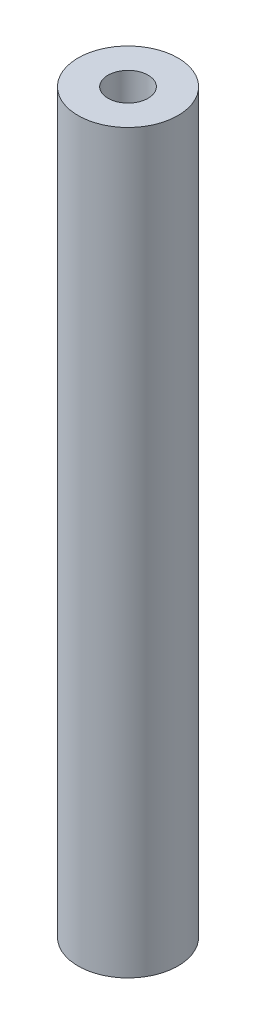
SolidWorks part; units mm, degrees
material "6061 Alloy"
ref_plane "Front" through (0, 0, 0) normal (0, 0, 1) x (1, 0, 0)
ref_plane "Top" through (0, 0, 0) normal (0, 1, 0) x (1, 0, 0)
ref_plane "Right" through (0, 0, 0) normal (1, 0, 0) x (0, 0, -1)
sketch "Sketch1" plane through (0, 0, 0) normal (0, 1, 0) x (1, 0, 0)
  circle A0 centre (0, 0) radius 6.35
  dimension "D1" = 12.7
extrude "Boss-Extrude1" add sketch "Sketch1" along normal blind 93.6625
hole_wizard "1/4-20 Tapped Hole1" positions "Sketch2" profile "Sketch3" tap size "1/4-20" standard "ANSI Inch"
sketch "Sketch2" plane through (0, 93.6625, 0) normal (0, 1, 0) x (1, 0, 0)
  point P0 (0, 0)
sketch "Sketch3" plane through (0, 93.6625, 0) normal (1, 0, 0) x (0, 0, 1)
  line L0 (0, 0) -> (0, 26.9338)
  line L1 (0, 26.9338) -> (2.5527, 25.4)
  line L2 (2.5527, 25.4) -> (2.5527, 0)
  line L5 (2.5527, 0) -> (0, 0)
  line L10 (0, 26.9338) -> (-2.5527, 25.4) construction
  line L11 (0, -6.35) -> (0, 107.95) construction
  dimension "Tap Drill Dia." = 5.1054
  dimension "Tap Drill Depth" = 25.4
  dimension "Drill Angle" = 118
cosmetic thread "Hole Thread1" parameters "D1"=21.59, "D2"=6.35
hole_wizard "1/4-20 Tapped Hole2" positions "Sketch4" profile "Sketch5" tap size "1/4-20" standard "ANSI Inch"
sketch "Sketch4" plane through (0, 0, 0) normal (0, -1, 0) x (-1, 0, 0)
  point P0 (0, 0)
sketch "Sketch5" plane through (0, 0, 0) normal (1, 0, 0) x (0, 0, -1)
  line L0 (0, 0) -> (0, 26.9338)
  line L1 (0, 26.9338) -> (2.5527, 25.4)
  line L2 (2.5527, 25.4) -> (2.5527, 0)
  line L5 (2.5527, 0) -> (0, 0)
  line L10 (0, 26.9338) -> (-2.5527, 25.4) construction
  line L11 (0, -6.35) -> (0, 107.95) construction
  dimension "Tap Drill Dia." = 5.1054
  dimension "Tap Drill Depth" = 25.4
  dimension "Drill Angle" = 118
cosmetic thread "Hole Thread2" parameters "D1"=21.59, "D2"=6.35
